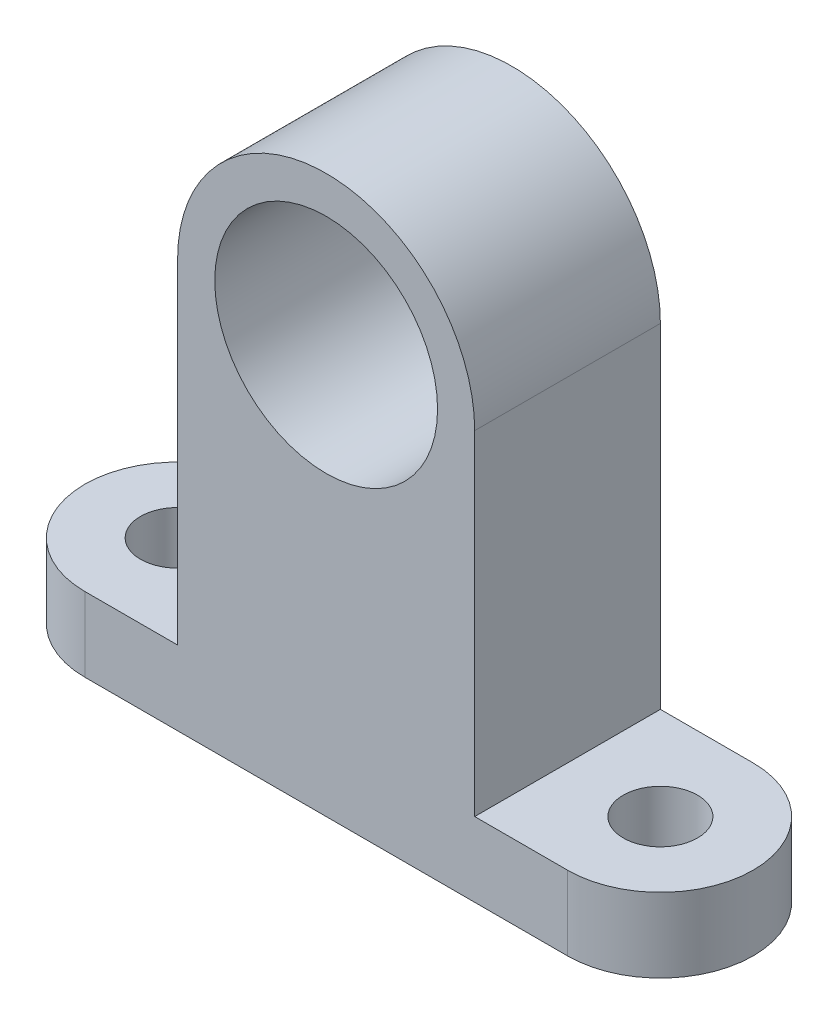
SolidWorks part; units mm, degrees
ref_plane "Front Plane" through (0, 0, 0) normal (0, 0, 1) x (1, 0, 0)
ref_plane "Top Plane" through (0, 0, 0) normal (0, 1, 0) x (1, 0, 0)
ref_plane "Right Plane" through (0, 0, 0) normal (1, 0, 0) x (0, 0, -1)
sketch "Sketch1" plane through (0, 0, 0) normal (0, 0, 1) x (1, 0, 0)
  line L0 (0, 0) -> (0, -457.2) construction
  line L1 (-203.2, -457.2) -> (203.2, -457.2)
  line L2 (-203.2, 0) -> (-203.2, -457.2)
  line L3 (203.2, 0) -> (203.2, -457.2)
  arc A0 (203.2, 0) -> (-203.2, 0) centre (0, 0) ccw
  circle A1 centre (0, 0) radius 152.4
  point P8 (0, -457.2)
  dimension "D1" = 406.4
  dimension "D2" = 304.8
  dimension "D3" = 457.2
  dimension "D4" = 406.4
  dimension "D5" = 457.2
extrude "Boss-Extrude1" add sketch "Sketch1" along normal mid plane 254
sketch "Sketch2" plane through (0, -457.2, 0) normal (0, -1, 0) x (1, 0, 0)
  line L1 (-203.2, -127) -> (203.2, -127) construction
  line L3 (-203.2, 127) -> (203.2, 127) construction
  line L5 (-203.2, -127) -> (203.2, -127)
  line L7 (-203.2, 127) -> (203.2, 127)
  line L8 (-330.2, 127) -> (-203.2, 127)
  line L9 (-330.2, -127) -> (-203.2, -127)
  line L10 (203.2, 127) -> (330.2, 127)
  line L11 (203.2, -127) -> (330.2, -127)
  arc A0 (-330.2, 127) -> (-330.2, -127) centre (-330.2, 0) ccw
  arc A1 (330.2, -127) -> (330.2, 127) centre (330.2, 0) ccw
  circle A2 centre (-330.2, 0) radius 50.8
  circle A3 centre (330.2, 0) radius 50.8
  dimension "D2" = 254
  dimension "D3" = 101.6
  dimension "D4" = 101.6
  dimension "D5" = 330.2
  dimension "D6" = 330.2
extrude "Boss-Extrude2" add sketch "Sketch2" along normal blind 101.6
